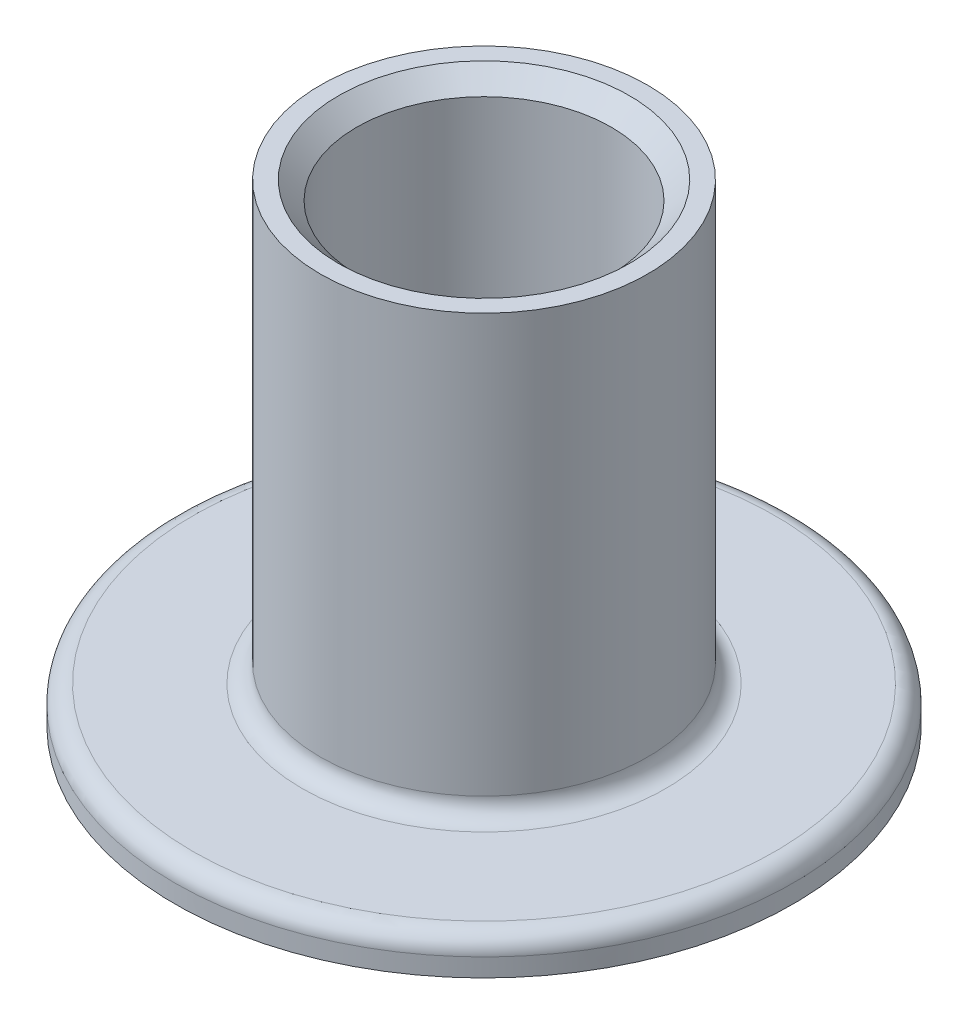
SolidWorks part; units mm, degrees
ref_plane "Front Plane" through (0, 0, 0) normal (0, 0, 1) x (1, 0, 0)
ref_plane "Top Plane" through (0, 0, 0) normal (0, 1, 0) x (1, 0, 0)
ref_plane "Right Plane" through (0, 0, 0) normal (1, 0, 0) x (0, 0, -1)
sketch "Sketch1" plane through (0, 0, 0) normal (0, 0, 1) x (1, 0, 0)
  line L0 (0, 0) -> (0, 147.4667) construction
  line L1 (0, 0) -> (42.5, 0)
  line L2 (42.5, 0) -> (42.5, 5)
  line L3 (42.5, 5) -> (22.5, 5)
  line L5 (22.5, 5.2988) -> (22.5, 65)
  line L6 (22.5, 65) -> (17.5, 65)
  line L7 (17.5, 65) -> (17.5, 22.8292)
  line L8 (17.5, 22.8292) -> (0, 5.3292)
  line L9 (0, 5.3292) -> (0, 0)
  line L10 (22.5, 5.2988) -> (22.5, 5)
  dimension "D1" = 17.5
  dimension "D2" = 5
  dimension "D3" = 5
  dimension "D4" = 20
  dimension "D5" = 135
  dimension "D6" = 65
revolve "Revolve1" add sketch "Sketch1" angle 360 about L0
fillet "Fillet1" radius 2.5 2 edges at (0, 5, -42.5) (0, 5, -22.5)
chamfer "Chamfer2" distance 2.5 angle 45 1 edges at (0, 65, -17.5)
